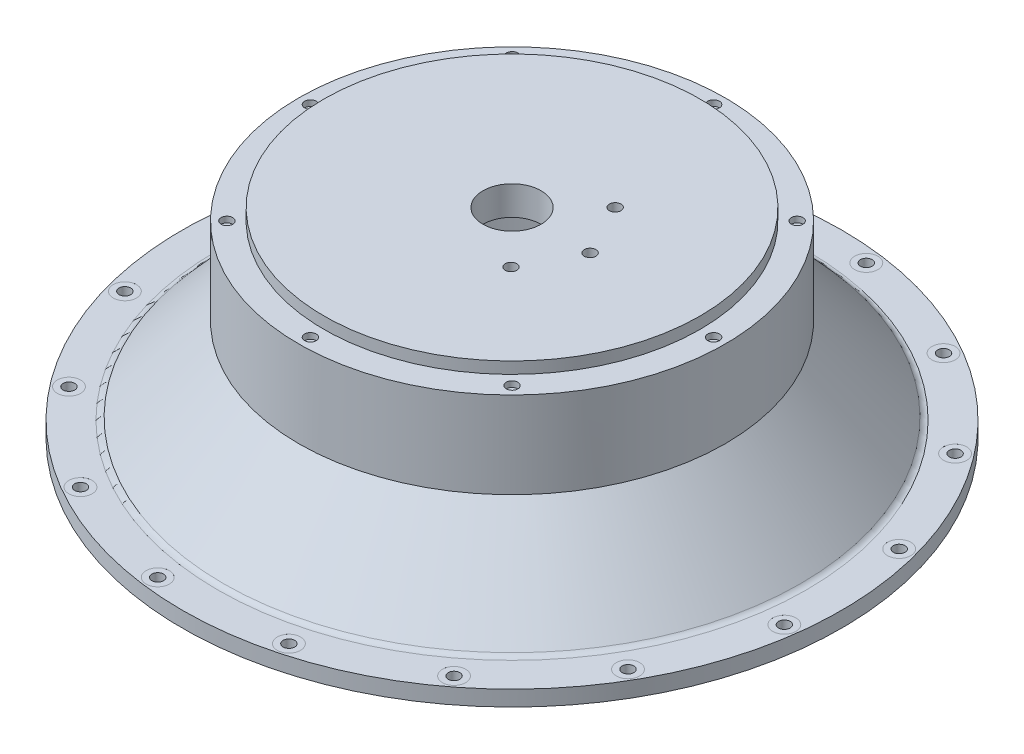
SolidWorks part; units mm, degrees
material "PF"
ref_plane "前视基准面" through (0, 0, 0) normal (0, 0, 1) x (1, 0, 0)
ref_plane "上视基准面" through (0, 0, 0) normal (0, 1, 0) x (1, 0, 0)
ref_plane "右视基准面" through (0, 0, 0) normal (1, 0, 0) x (0, 0, -1)
sketch "草图1" plane through (0, 0, 0) normal (0, 1, 0) x (1, 0, 0)
  circle A0 centre (0, 0) radius 85
  dimension "D1" = 170
extrude "凸台-拉伸1" add sketch "草图1" along normal blind 4
sketch "草图2" plane through (0, 4, 0) normal (0, 1, 0) x (1, 0, 0)
  circle A0 centre (0, 0) radius 56.4
  dimension "D1" = 112.8
extrude "切除-拉伸1" cut sketch "草图2" against normal blind 50
sketch "草图3" plane through (0, 0, 0) normal (0, 0, 1) x (1, 0, 0)
  line L10 (0, 4) -> (-75, 4)
  line L11 (56.4, 4) -> (-56.4, 4) construction
  line L12 (85, 4) -> (-85, 4) construction
  line L13 (-75, 4) -> (-52.5, 29)
  line L14 (-52.5, 29) -> (0, 29)
  line L15 (0, 29) -> (0, 4)
  dimension "D1" = 52.5
  dimension "D2" = 75
  dimension "D3" = 25
revolve "旋转1" add sketch "草图3" angle 360 about L15
sketch "草图6" plane through (0, 4, 0) normal (0, -1, 0) x (1, 0, 0)
  circle A0 centre (0, 0) radius 56.4
sketch "草图7" plane through (0, 0, 0) normal (0, 0, 1) x (1, 0, 0)
  line L0 (-70.9639, 4) -> (-48.4639, 29)
  line L1 (85, 4) -> (-85, 4) construction
  line L2 (52.5, 29) -> (-52.5, 29) construction
  line L3 (-48.4639, 29) -> (0, 29)
  line L4 (0, 29) -> (0, 4)
  line L5 (-56.4, 4) -> (56.4, 4) construction
  line L6 (0, 4) -> (-70.9639, 4)
revolve "切除-旋转1" cut sketch "草图7" angle 360 about L4
sketch "草图8" plane through (0, 0, 0) normal (0, -1, 0) x (1, 0, 0)
  circle A0 centre (0, 0) radius 56.4
  circle A1 centre (0, 0) radius 68.9569
extrude "凸台-拉伸2" add sketch "草图8" against normal up to surface (20.1821 mm away)
sketch "草图9" plane through (0, 4, 0) normal (0, 1, 0) x (1, 0, 0)
  circle A0 centre (-40.694, -70.6134) radius 1.5
extrude "切除-拉伸3" cut sketch "草图9" against normal blind 5000
pattern_circular "阵列(圆周)1" count 16 over 360 about axis through (0, 0, 0) along (0, 1, 0) of "切除-拉伸3"
sketch "草图11" plane through (0, 29, 0) normal (0, 1, 0) x (1, 0, 0)
  circle A0 centre (0, 0) radius 48.4639
  circle A1 centre (0, 0) radius 52.5
  circle A2 centre (0, 0) radius 48.4639 construction
  circle A3 centre (0, 0) radius 52.5 construction
extrude "凸台-拉伸3" add sketch "草图11" along normal blind 30
sketch "草图12" plane through (0, 59, 0) normal (0, 1, 0) x (1, 0, 0)
  circle A0 centre (0, 0) radius 52.5
  circle A1 centre (0, 0) radius 22.5
  circle A2 centre (0, 0) radius 52.5 construction
  dimension "D1" = 45
extrude "凸台-拉伸4" add sketch "草图12" along normal blind 5
fillet "圆角1" radius 2 1 edges at (-75, 4, 0)
sketch "草图13" plane through (0, 0, 0) normal (0, -1, 0) x (1, 0, 0)
  circle A0 centre (0, 0) radius 56.4
  circle A1 centre (0, 0) radius 85
extrude "凸台-拉伸5" add sketch "草图13" along normal blind 1
sketch "草图14" plane through (0, 4, 0) normal (0, 1, 0) x (1, 0, 0)
  circle A0 centre (-70.6134, 40.694) radius 1.5
extrude "切除-拉伸4" cut sketch "草图14" against normal blind 50
pattern_circular "阵列(圆周)2" count 16 over 360 about axis through (0, 0, 0) along (0, 1, 0) of "切除-拉伸4"
chamfer "倒角2" distance 5 angle 45 1 edges at (-48.4639, 59, 0)
sketch "草图15" plane through (0, 64, 0) normal (0, 1, 0) x (1, 0, 0)
  circle A0 centre (0, 0) radius 43
  circle A1 centre (0, 0) radius 45
  dimension "D1" = 86
  dimension "D2" = 90
extrude "切除-拉伸5" cut sketch "草图15" against normal blind 2
sketch "草图16" plane through (0, 64, 0) normal (0, 1, 0) x (1, 0, 0)
  circle A0 centre (0, 0) radius 22.5
  circle A1 centre (0, 0) radius 15
  dimension "D1" = 30
extrude "凸台-拉伸6" add sketch "草图16" against normal up to surface (5 mm away) up to face at (-43.4639, 59, 0)
sketch "草图17" plane through (0, 64, 0) normal (0, 1, 0) x (1, 0, 0)
  circle A0 centre (13.1611, -13.4275) radius 1.5
  circle A1 centre (20.2143, -0.0805) radius 1.5
  circle A2 centre (13.2676, 13.3223) radius 1.5
sketch "草图18" plane through (0, 4, 0) normal (0, 1, 0) x (1, 0, 0)
  circle A0 centre (-80.8112, 10.5738) radius 3
  dimension "D1" = 6
extrude "切除-拉伸7" cut sketch "草图18" against normal blind 0.002
pattern_circular "阵列(圆周)3" count 16 over 360 about axis through (0, 0, 0) along (0, 1, 0) of "切除-拉伸7"
sketch "草图19" plane through (0, 64, 0) normal (0, 1, 0) x (1, 0, 0)
  circle A0 centre (0, 0) radius 55
  circle A1 centre (0, 0) radius 49.1281
  dimension "D1" = 110
extrude "凸台-拉伸7" add sketch "草图19" against normal up to surface (37.7778 mm away)
sketch "草图20" plane through (0, 64, 0) normal (0, 1, 0) x (1, 0, 0)
  circle A0 centre (0, 0) radius 36.4679
  circle A1 centre (0, 0) radius 47.9092
extrude "凸台-拉伸9" add sketch "草图20" against normal blind 2
sketch "草图21" plane through (0, 64, 0) normal (0, 1, 0) x (1, 0, 0)
  circle A0 centre (0, 0) radius 61.0105
extrude "切除-拉伸8" cut sketch "草图21" against normal blind 15
sketch "草图22" plane through (0, 49, 0) normal (0, 1, 0) x (1, 0, 0)
  circle A0 centre (0, 0) radius 55
extrude "凸台-拉伸11" add sketch "草图22" against normal blind 5
sketch "草图23" plane through (0, 49, 0) normal (0, 1, 0) x (1, 0, 0)
  line L0 (-121.5585, 0) -> (129.0789, 0) construction
  line L1 (0, 130.6355) -> (0, -173.8496) construction
  circle A0 centre (52, 0) radius 1.5
  circle A1 centre (0, 0) radius 55 construction
  point P9 (55, 0)
  dimension "D1" = 3
  dimension "D2" = 3
extrude "切除-拉伸9" cut sketch "草图23" against normal blind 2
pattern_circular "阵列(圆周)4" count 8 over 360 about axis through (0, 0, 0) along (0, 1, 0) of "切除-拉伸9"
sketch "草图24" plane through (0, 49, 0) normal (0, 1, 0) x (1, 0, 0)
  circle A0 centre (0, 0) radius 48.5
  circle A1 centre (0, 0) radius 55 construction
  dimension "D1" = 6.5
extrude "凸台-拉伸12" add sketch "草图24" along normal blind 3
sketch "草图25" plane through (0, 52, 0) normal (0, 1, 0) x (1, 0, 0)
  circle A0 centre (0, 0) radius 7.5
  dimension "D1" = 15
extrude "切除-拉伸10" cut sketch "草图25" against normal blind 500
sketch "草图26" plane through (0, -1, 0) normal (0, -1, 0) x (1, 0, 0)
  circle A0 centre (0, 0) radius 99.3771
extrude "切除-拉伸11" cut sketch "草图26" against normal blind 1
sketch "草图27" plane through (0, 49, 0) normal (0, 1, 0) x (1, 0, 0)
  circle A0 centre (0, 0) radius 48.5
  circle A1 centre (0, 0) radius 55
extrude "切除-拉伸13" cut sketch "草图27" against normal blind 0.5
sketch "草图28" plane through (0, 52, 0) normal (0, 1, 0) x (1, 0, 0)
  circle A0 centre (0, 0) radius 50.33
extrude "切除-拉伸14" cut sketch "草图28" against normal blind 0.5
extrude "切除-拉伸17" cut sketch "草图17" against normal blind 20 contours A0 | A1 | A2
